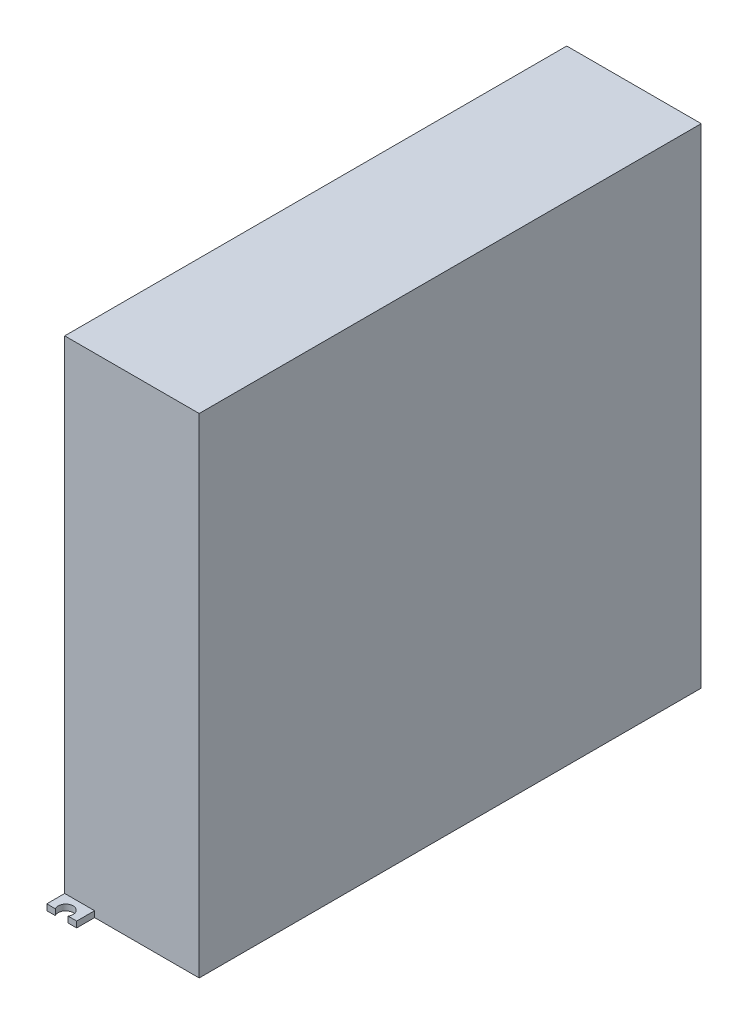
SolidWorks part; units mm, degrees
ref_plane "前视基准面" through (0, 0, 0) normal (0, 0, 1) x (1, 0, 0)
ref_plane "上视基准面" through (0, 0, 0) normal (0, 1, 0) x (1, 0, 0)
ref_plane "右视基准面" through (0, 0, 0) normal (1, 0, 0) x (0, 0, -1)
other "Configuration Table"
sketch "草图1" plane through (0, 0, 0) normal (0, 1, 0) x (1, 0, 0)
  line L1 (0, 0) -> (45, 0)
  line L2 (0, 0) -> (0, -168)
  line L3 (0, -168) -> (45, -168)
  line L4 (45, 0) -> (45, -168)
extrude "凸台-拉伸1" add sketch "草图1" along normal blind 163.6
sketch "草图2" plane through (0, 0, 0) normal (0, -1, 0) x (1, 0, 0)
  line L0 (0, 168) -> (0, 174)
  line L1 (0, 174) -> (10, 174)
  line L2 (10, 174) -> (10, 168)
  line L3 (0, 168) -> (45, 168) construction
  line L4 (0, 168) -> (10, 168)
extrude "凸台-拉伸2" add sketch "草图2" against normal blind 2
hole_wizard "Ø5.0mm 暗销孔1" positions "草图3" profile "草图4" hole size "Ø5.0" standard "GB" end condition through all
sketch "草图3" plane through (0, 0, 0) normal (0, -1, 0) x (-1, 0, 0)
  line L0 (-45, -168) -> (-45, 0) construction
  point P0 (-5, -172.6777)
  point P5 (-5, -174.7327)
  point P6 (-5, -172.6777)
  dimension "D1" = 40
sketch "草图4" plane through (5, 0, 172.6777) normal (1, 0, 0) x (0, 0, -1)
  line L0 (0, 0) -> (0, 163.6)
  line L1 (0, 163.6) -> (2.5, 163.6)
  line L2 (2.5, 163.6) -> (2.5, 0.021)
  line L3 (2.5, 0.021) -> (2.525, 0)
  line L5 (2.525, 0) -> (0, 0)
  line L6 (-2.5, 0.021) -> (-2.525, 0) construction
  line L11 (0, -6.35) -> (0, 107.95) construction
  dimension "通孔孔直径" = 5
  dimension "通孔孔深度" = 163.6
  dimension "近端锥形沉头孔直径" = 5.05
  dimension "近端锥形沉头孔角度" = 100
